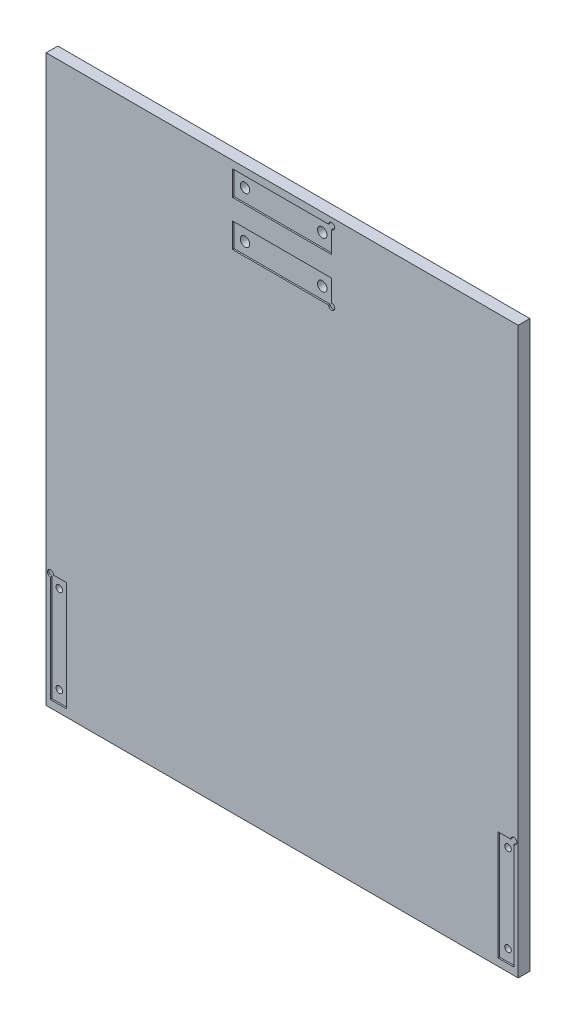
SolidWorks part; units mm, degrees
ref_plane "Plan de face" through (0, 0, 0) normal (0, 0, 1) x (1, 0, 0)
ref_plane "Plan de dessus" through (0, 0, 0) normal (0, 1, 0) x (1, 0, 0)
ref_plane "Plan de droite" through (0, 0, 0) normal (1, 0, 0) x (0, 0, -1)
sketch "Esquisse1" plane through (0, 0, 0) normal (0, 0, 1) x (1, 0, 0)
  line L0 (0, 100.453) -> (0, -98.9703) construction
  line L2 (-162, 194) -> (162, 194)
  line L3 (-162, 194) -> (-162, -194)
  line L4 (-162, -194) -> (162, -194)
  line L5 (162, 194) -> (162, -194)
  line L6 (-162, 194) -> (162, -194) construction
  line L7 (-162, -194) -> (162, 194) construction
  point P3 (0, 0)
  dimension "D1" = 324
  dimension "D2" = 388
extrude "Boss.-Extru.1" add sketch "Esquisse1" along normal blind 8
sketch "Esquisse2" plane through (0, 0, 8) normal (0, 0, 1) x (1, 0, 0)
  line L1 (148, -114) -> (156.9, -114)
  line L2 (148, -114) -> (148, -189)
  line L3 (148, -189) -> (159, -189)
  line L4 (159, -116.1) -> (159, -189)
  line L5 (148, -114) -> (159, -189) construction
  line L6 (148, -189) -> (159, -114) construction
  line L7 (162, -194) -> (162, 194) construction
  line L8 (-162, -194) -> (162, -194) construction
  arc A0 (156.9, -114) -> (159, -116.1) centre (159, -114) cw
  point P0 (153.5, -151.5)
  point P6 (150, -114)
  point P7 (155.5, -151.5)
  dimension "D5" = 2.1
  dimension "D1" = 75
  dimension "D2" = 11
  dimension "D3" = 5
  dimension "D4" = 3
extrude "Enlèv. mat.-Extru.1" cut sketch "Esquisse2" against normal blind 1
mirror "Symétrie1" about plane through (0, 0, 0) normal (1, 0, 0) of "Enlèv. mat.-Extru.1"
sketch "Esquisse3" plane through (0, 0, 7) normal (0, 0, 1) x (1, 0, 0)
  line L0 (233.6999, -151) -> (115.0156, -151) construction
  line L1 (156.9, -114) -> (148, -114) construction
  line L2 (159, -189) -> (159, -116.1) construction
  circle A0 centre (154, -121) radius 2.25
  circle A1 centre (154, -181) radius 2.25
  dimension "D3" = 4.5
  dimension "D6" = 4.5
  dimension "D1" = 7
  dimension "D2" = 5
  dimension "D4" = 37
  dimension "D5" = 30
extrude "Enlèv. mat.-Extru.2" cut sketch "Esquisse3" against normal through all
mirror "Symétrie2" about plane through (0, 0, 0) normal (1, 0, 0) of "Enlèv. mat.-Extru.2"
sketch "Esquisse4" plane through (0, 0, 8) normal (0, 0, 1) x (1, 0, 0)
  line L0 (0, 11.5039) -> (0, 55.69) construction
  line L1 (-34, 189) -> (31.9, 189)
  line L2 (-34, 189) -> (-34, 172)
  line L3 (-34, 172) -> (34, 172)
  line L4 (34, 186.9) -> (34, 172)
  line L5 (-34, 189) -> (34, 172) construction
  line L6 (-34, 172) -> (34, 189) construction
  line L7 (162, 194) -> (-162, 194) construction
  line L8 (-40.9309, 165) -> (56.3141, 165) construction
  line L9 (-34, 158) -> (34, 141) construction
  line L10 (-34, 141) -> (34, 158) construction
  line L15 (34, 143.1) -> (34, 158)
  line L16 (-34, 158) -> (34, 158)
  line L17 (-34, 141) -> (-34, 158)
  line L18 (-34, 141) -> (31.9, 141)
  arc A0 (31.9, 189) -> (34, 186.9) centre (34, 189) cw
  arc A1 (31.9, 141) -> (34, 143.1) centre (34, 141) ccw
  point P0 (0, 180.5)
  point P21 (0, 149.5)
  dimension "D5" = 2.1
  dimension "D1" = 68
  dimension "D2" = 17
  dimension "D3" = 5
  dimension "D4" = 7
extrude "Enlèv. mat.-Extru.3" cut sketch "Esquisse4" against normal blind 1
sketch "Esquisse5" plane through (0, 0, 7) normal (0, 0, 1) x (1, 0, 0)
  line L0 (0, 43.9553) -> (0, 15.1111) construction
  line L1 (31.9, 189) -> (-34, 189) construction
  line L2 (-37.557, 165) -> (44.5617, 165) construction
  circle A0 centre (-26.5, 181) radius 3.25
  circle A1 centre (26.5, 181) radius 3.25
  circle A2 centre (26.5, 149) radius 3.25
  circle A3 centre (-26.5, 149) radius 3.25
  dimension "D3" = 6.5
  dimension "D2" = 8
  dimension "D4" = 7
extrude "Enlèv. mat.-Extru.4" cut sketch "Esquisse5" against normal through all
